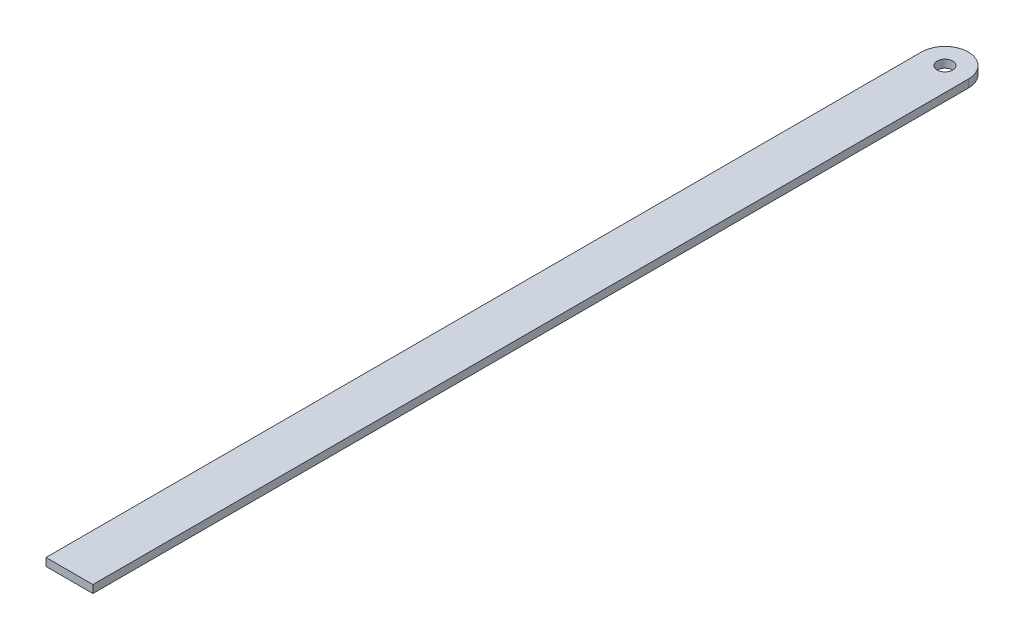
SolidWorks part; units mm, degrees
ref_plane "Front Plane" through (0, 0, 0) normal (0, 0, 1) x (1, 0, 0)
ref_plane "Top Plane" through (0, 0, 0) normal (0, 1, 0) x (1, 0, 0)
ref_plane "Right Plane" through (0, 0, 0) normal (1, 0, 0) x (0, 0, -1)
sketch "Sketch1" plane through (0, 0, 0) normal (0, 1, 0) x (1, 0, 0)
  line L2 (0, 0) -> (0, -177.8)
  line L3 (0, -177.8) -> (9.525, -177.8)
  line L4 (9.525, 0) -> (9.525, -177.8)
  circle A0 centre (4.7625, 0) radius 1.5875
  arc A1 (0, 0) -> (9.525, 0) centre (4.7625, 0) cw
  dimension "D3" = 3.175
  dimension "D1" = 177.8
  dimension "D2" = 9.525
extrude "Boss-Extrude1" add sketch "Sketch1" along normal blind 1.5875
